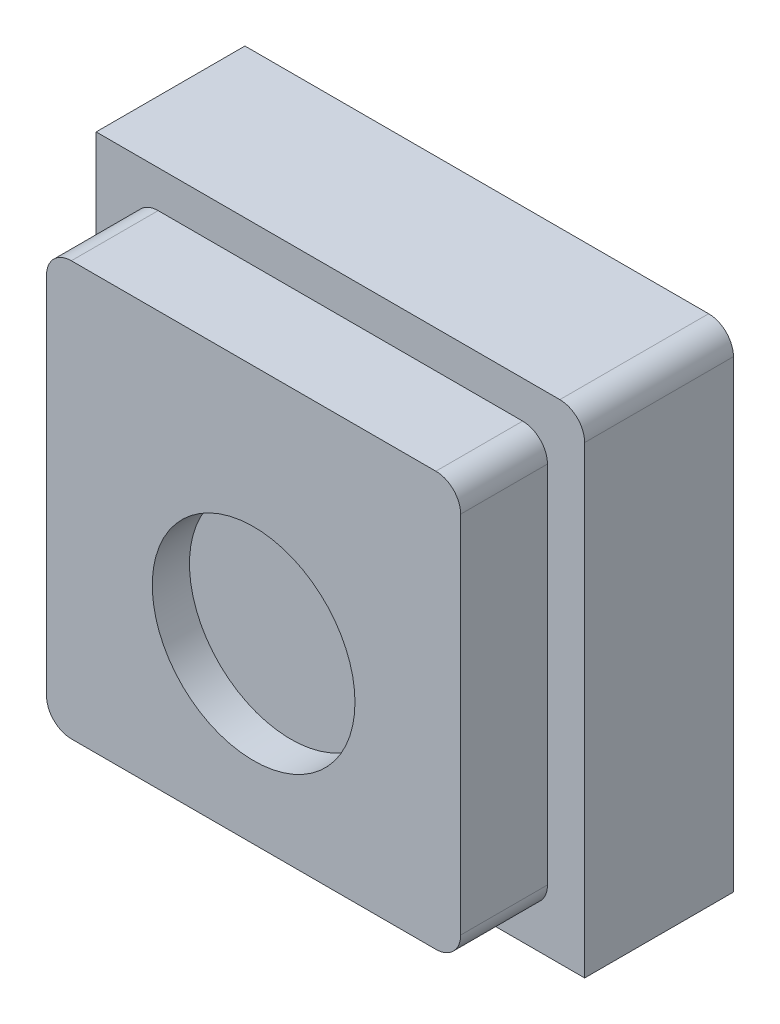
SolidWorks part; units mm, degrees
ref_plane "Plan de face" through (0, 0, 0) normal (0, 0, 1) x (1, 0, 0)
ref_plane "Plan de dessus" through (0, 0, 0) normal (0, 1, 0) x (1, 0, 0)
ref_plane "Plan de droite" through (0, 0, 0) normal (1, 0, 0) x (0, 0, -1)
sketch "Esquisse1" plane through (0, 0, 0) normal (0, 0, 1) x (1, 0, 0)
  line L1 (-16.7, 16.7) -> (16.7, 16.7)
  line L2 (-16.7, 16.7) -> (-16.7, -16.7)
  line L3 (-16.7, -16.7) -> (16.7, -16.7)
  line L4 (16.7, 16.7) -> (16.7, -16.7)
  point P4 (0, 16.7)
  point P5 (-16.7, 0)
  dimension "D1" = 33.4
  dimension "D2" = 33.4
extrude "Boss.-Extru.1" add sketch "Esquisse1" along normal blind 7
sketch "Esquisse2" plane through (0, 0, 7) normal (0, 0, 1) x (1, 0, 0)
  line L0 (-16.7, -16.7) -> (16.7, -16.7) construction
  circle A0 centre (0, -2.7) radius 8.175
  dimension "D1" = 16.35
  dimension "D2" = 14
extrude "Enlèv. mat.-Extru.1" cut sketch "Esquisse2" against normal blind 3
sketch "Esquisse3" plane through (0, 0, 0) normal (0, 0, -1) x (-1, 0, 0)
  line L0 (-16.7, 16.7) -> (16.7, 16.7) construction
  line L1 (-19.7, 19.7) -> (19.7, 19.7)
  line L2 (-19.7, 19.7) -> (-19.7, -19.7)
  line L3 (-19.7, -19.7) -> (19.7, -19.7)
  line L4 (19.7, 19.7) -> (19.7, -19.7)
  line L5 (-16.7, -16.7) -> (-16.7, 16.7) construction
  line L6 (16.7, -16.7) -> (-16.7, -16.7) construction
  line L7 (16.7, 16.7) -> (16.7, -16.7) construction
  dimension "D1" = 3
  dimension "D2" = 3
  dimension "D3" = 3
  dimension "D4" = 3
extrude "Boss.-Extru.2" add sketch "Esquisse3" along normal blind 2
sketch "Esquisse4" plane through (0, 0, -2) normal (0, 0, -1) x (-1, 0, 0)
  line L0 (19.7, 19.7) -> (-19.7, 19.7)
  line L1 (-19.7, 19.7) -> (-19.7, -19.7)
  line L2 (-19.7, -19.7) -> (-16.7, -19.7)
  line L3 (-19.7, -19.7) -> (19.7, -19.7) construction
  line L4 (-16.7, -19.7) -> (-16.7, 16.7)
  line L5 (-16.7, 16.7) -> (19.7, 16.7)
  line L6 (19.7, -19.7) -> (19.7, 19.7) construction
  line L7 (19.7, 16.7) -> (19.7, 19.7)
  dimension "D1" = 3
  dimension "D2" = 3
extrude "Boss.-Extru.3" add sketch "Esquisse4" along normal blind 10
fillet "Congé1" radius 2 5 edges at (16.7, -16.7, 3.5) (16.7, 16.7, 3.5) (-16.7, 16.7, 3.5) (-16.7, -16.7, 3.5) (19.7, 19.7, -6)
